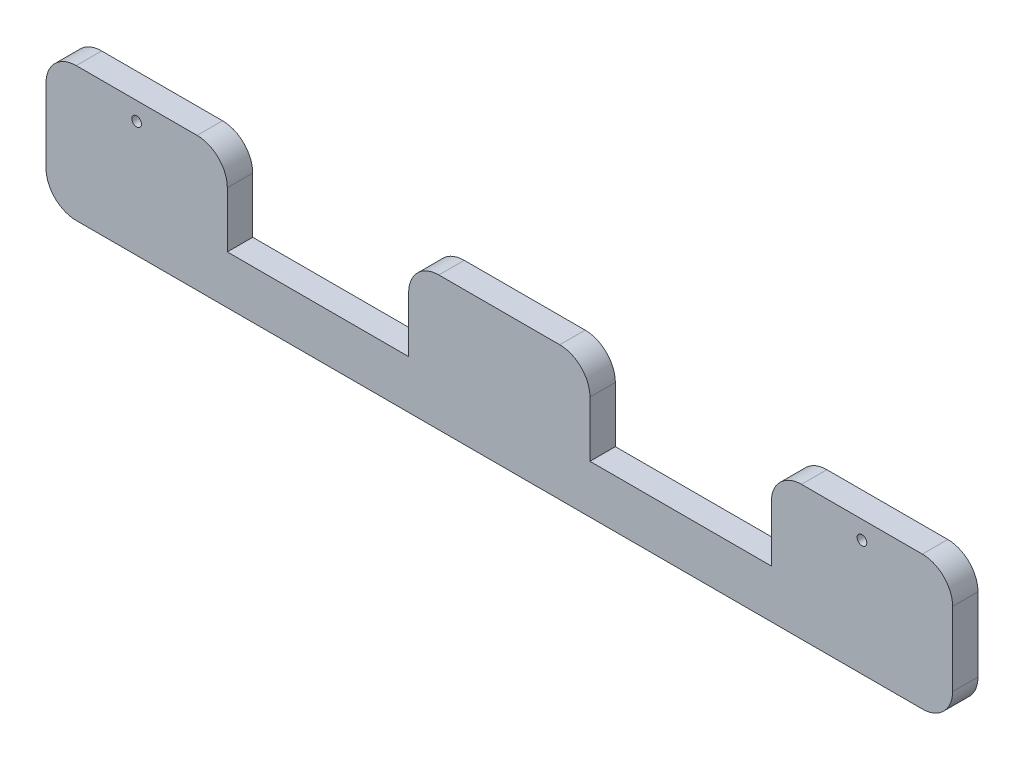
SolidWorks part; units mm, degrees
ref_plane "Front Plane" through (0, 0, 0) normal (0, 0, 1) x (1, 0, 0)
ref_plane "Top Plane" through (0, 0, 0) normal (0, 1, 0) x (1, 0, 0)
ref_plane "Right Plane" through (0, 0, 0) normal (1, 0, 0) x (0, 0, -1)
sketch "Sketch1" plane through (0, 0, 0) normal (0, 0, 1) x (1, 0, 0)
  line L1 (-85.0624, -31.2608) -> (105.4376, -31.2608)
  line L2 (-85.0624, -31.2608) -> (-85.0624, -59.4548)
  line L3 (-85.0624, -59.4548) -> (105.4376, -59.4548)
  line L4 (105.4376, -31.2608) -> (105.4376, -59.4548)
  dimension "D1" = 190.5
  dimension "D2" = 28.194
extrude "Boss-Extrude1" add sketch "Sketch1" along normal blind 5.334
sketch "Sketch3" plane through (0, 0, 5.334) normal (0, 0, 1) x (1, 0, 0)
  line L0 (105.4376, -31.2608) -> (-85.0624, -31.2608) construction
  line L1 (-46.9624, -31.2608) -> (-8.8624, -31.2608)
  line L2 (-46.9624, -31.2608) -> (-46.9624, -49.2948)
  line L3 (-46.9624, -49.2948) -> (-8.8624, -49.2948)
  line L4 (-8.8624, -31.2608) -> (-8.8624, -49.2948)
  line L5 (-8.8624, -49.2948) -> (29.2376, -49.2948) construction
  line L6 (29.2376, -31.2608) -> (67.3376, -31.2608)
  line L7 (29.2376, -31.2608) -> (29.2376, -49.2948)
  line L8 (29.2376, -49.2948) -> (67.3376, -49.2948)
  line L9 (67.3376, -31.2608) -> (67.3376, -49.2948)
  line L10 (67.3376, -49.2948) -> (105.4376, -49.2948) construction
  line L11 (105.4376, -59.4548) -> (105.4376, -31.2608) construction
  line L12 (-46.9624, -49.2948) -> (-85.0624, -49.2948) construction
  line L13 (-85.0624, -31.2608) -> (-85.0624, -59.4548) construction
  dimension "D1" = 18.034
extrude "Cut-Extrude1" cut sketch "Sketch3" against normal through all
sketch "Sketch4" plane through (0, 0, 5.334) normal (0, 0, 1) x (1, 0, 0)
  line L0 (-46.9624, -31.2608) -> (-85.0624, -31.2608) construction
  line L1 (-46.9624, -31.2608) -> (-46.9624, -49.2948) construction
  line L2 (10.1876, -31.2608) -> (10.1876, -59.4548) construction
  line L3 (29.2376, -31.2608) -> (-8.8624, -31.2608) construction
  line L4 (-85.0624, -59.4548) -> (105.4376, -59.4548) construction
  circle A0 centre (-66.0124, -35.0708) radius 1.016
  circle A1 centre (86.3876, -35.0708) radius 1.016
  dimension "D1" = 2.032
  dimension "D2" = 3.81
  dimension "D3" = 19.05
extrude "Cut-Extrude2" cut sketch "Sketch4" against normal through all
fillet "Fillet1" radius 6.35 8 edges at (29.2376, -31.2608, 2.667) (-8.8624, -31.2608, 2.667) (-46.9624, -31.2608, 2.667) (67.3376, -31.2608, 2.667) (105.4376, -31.2608, 2.667) (105.4376, -59.4548, 2.667) (-85.0624, -59.4548, 2.667) (-85.0624, -31.2608, 2.667)
equation "\"MDF\"= .21in"
equation "\"Foamcore\"= .13in"
equation "\"Gmaterial\"= \"MDF\""
equation "\"D2@Sketch1\"=\"MDF\"+.4+.5"
equation "\"D1@Boss-Extrude1\"=\"MDF\""
equation "\"D1@Sketch3\"=\"MDF\"+0.5"
